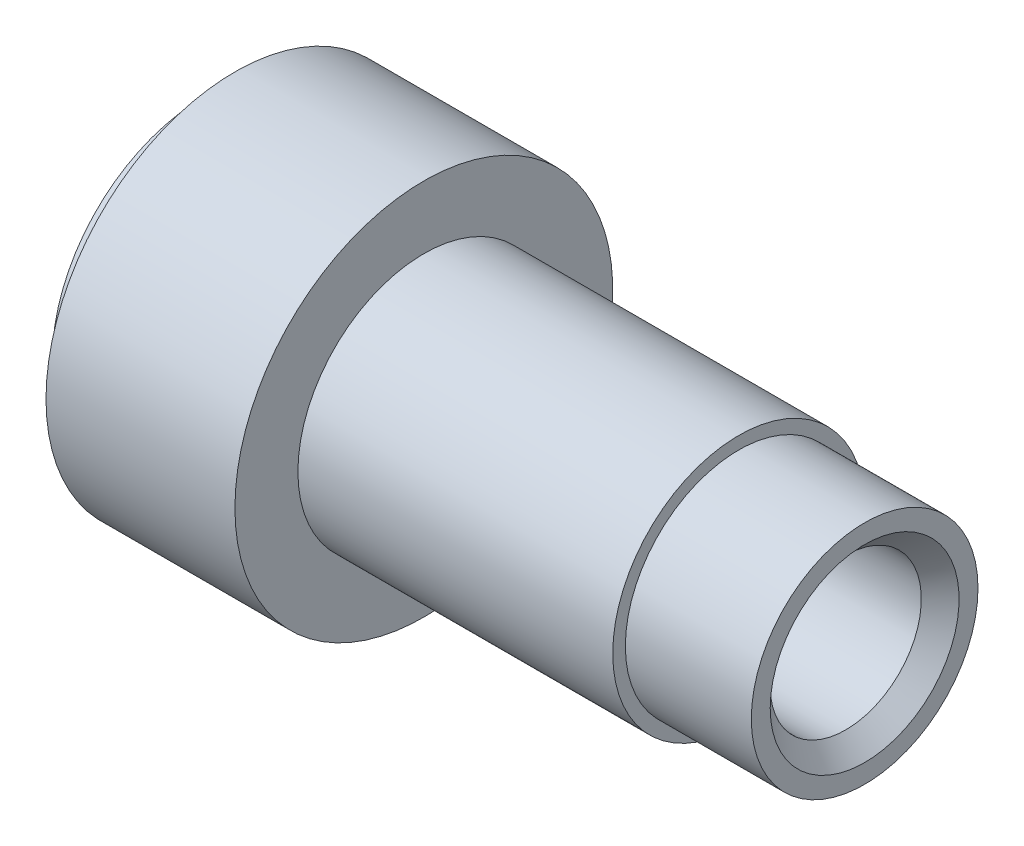
SolidWorks part; units mm, degrees
ref_plane "Ebene vorne" through (0, 0, 0) normal (0, 0, 1) x (1, 0, 0)
ref_plane "Ebene oben" through (0, 0, 0) normal (0, 1, 0) x (1, 0, 0)
ref_plane "Ebene rechts" through (0, 0, 0) normal (1, 0, 0) x (0, 0, -1)
sketch "Skizze1" plane through (0, 0, 0) normal (0, 0, 1) x (1, 0, 0)
  line L0 (0, 0) -> (116.4916, 0) construction
  line L1 (3.4821, -20) -> (13.4821, -20)
  line L2 (13.4821, -18) -> (33.4821, -18)
  line L3 (33.4821, -18) -> (33.4821, -12)
  line L4 (33.4821, -12) -> (105.4821, -12)
  line L5 (108.4821, -15) -> (108.4821, -18)
  line L6 (108.4821, -18) -> (88.4821, -18)
  line L7 (88.4821, -18) -> (88.4821, -20)
  line L8 (88.4821, -20) -> (38.4821, -20)
  line L9 (38.4821, -20) -> (38.4821, -30)
  line L10 (38.4821, -30) -> (8.4821, -30)
  line L11 (8.4821, -30) -> (8.4821, -24)
  line L12 (8.4821, -24) -> (3.4821, -24)
  line L13 (3.4821, -24) -> (3.4821, -20)
  line L14 (13.4821, -20) -> (13.4821, -18)
  line L15 (105.4821, -12) -> (108.4821, -15)
  point P7 (23.4821, -18)
  point P9 (108.4821, -12)
  dimension "D1" = 105
  dimension "D2" = 20
  dimension "D3" = 30
  dimension "D4" = 5
  dimension "D5" = 20
  dimension "D6" = 10
  dimension "D7" = 12
  dimension "D8" = 18
  dimension "D9" = 20
  dimension "D10" = 18
  dimension "D11" = 20
  dimension "D12" = 24
  dimension "D13" = 30
revolve "Rotation1" add sketch "Skizze1" angle 360 about L0
